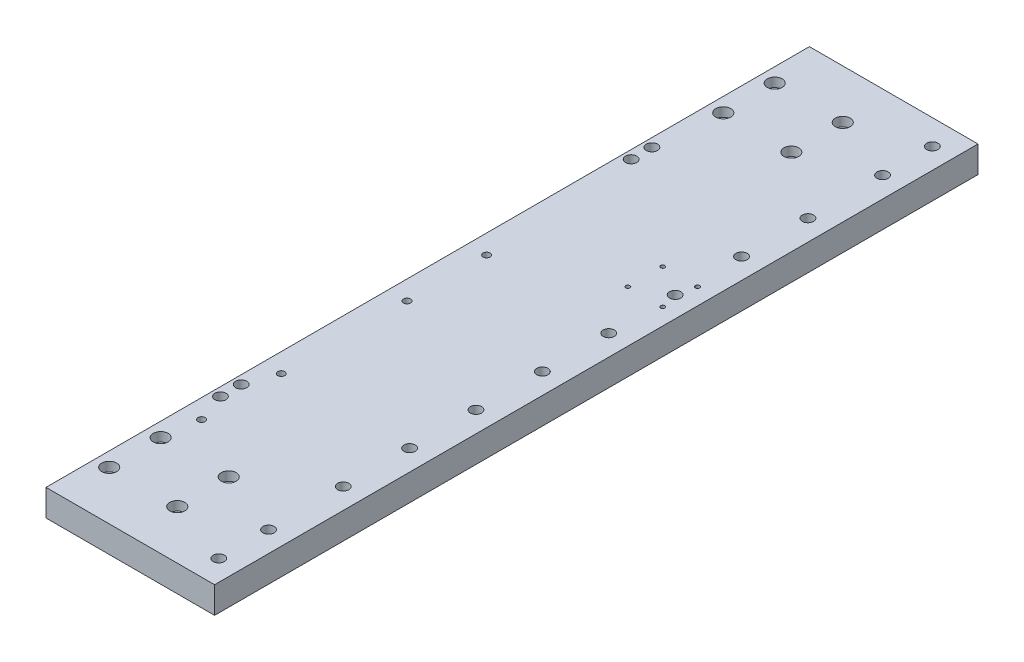
SolidWorks part; units mm, degrees
material "Low Carbon Steel"
ref_plane "Front Plane" through (0, 0, 0) normal (0, 0, 1) x (1, 0, 0)
ref_plane "Top Plane" through (0, 0, 0) normal (0, 1, 0) x (1, 0, 0)
ref_plane "Right Plane" through (0, 0, 0) normal (1, 0, 0) x (0, 0, -1)
sketch "Sketch1" plane through (0, 0, 0) normal (0, 1, 0) x (1, 0, 0)
  line L0 (0, 0) -> (0, 920)
  line L1 (0, 920) -> (203.2, 920)
  line L2 (203.2, 920) -> (203.2, 0)
  line L5 (203.2, 0) -> (0, 0)
  dimension "D1" = 920
  dimension "D2" = 203.2
extrude "Boss-Extrude1" add sketch "Sketch1" along normal blind 50.8
sketch "Sketch2" plane through (0, 0, -920) normal (0, 0, -1) x (-1, 0, 0)
  line L1 (-203.2, 5) -> (0, 5)
  line L2 (-203.2, 5) -> (-203.2, 0)
  line L3 (-203.2, 0) -> (0, 0)
  line L4 (0, 5) -> (0, 0)
  line L5 (0, 50.8) -> (0, 0) construction
  dimension "D1" = 5
extrude "Cut-Extrude1" cut sketch "Sketch2" against normal through all
sketch "Sketch6" plane through (0, 0, -920) normal (0, 0, -1) x (-1, 0, 0)
  line L1 (-203.2, 37) -> (52.8, 37)
  line L2 (-203.2, 37) -> (-203.2, 50.8)
  line L3 (-203.2, 50.8) -> (52.8, 50.8)
  line L4 (52.8, 37) -> (52.8, 50.8)
  line L5 (0, 5) -> (-203.2, 5) construction
  dimension "D1" = 256
  dimension "D2" = 32
extrude "Cut-Extrude3" cut sketch "Sketch6" against normal through all
hole_wizard "M12 Clearance Hole1" positions "Sketch8" profile "Sketch7" hole size "M12" standard "Peddi DIN" end condition through all
sketch "Sketch8" plane through (7.928, 37, -192.8709) normal (0, -1, 0) x (-1, 0, 0)
  line L0 (-170.272, 727.1291) -> (-170.272, -192.8709) construction
  line L6 (-195.272, 727.1291) -> (7.928, 727.1291) construction
  line L7 (-195.272, -192.8709) -> (-195.272, 727.1291) construction
  line L9 (-195.272, -192.8709) -> (7.928, -192.8709) construction
  point P10 (-170.272, 697.1291)
  point P12 (-170.272, 637.1291)
  point P14 (-170.272, 547.1291)
  point P16 (-170.272, 467.1291)
  point P18 (-170.272, 307.1291)
  point P29 (-170.272, 147.1291)
  point P32 (-170.272, 67.1291)
  point P41 (-170.272, -102.8709)
  point P42 (-170.272, 387.1291)
  point P44 (-170.272, 227.1291)
  point P46 (-170.272, -12.8709)
  point P49 (-170.272, -162.8709)
  dimension "D1" = 30
  dimension "D2" = 25
  dimension "D3" = 60
  dimension "D4" = 90
  dimension "D5" = 80
  dimension "D6" = 80
  dimension "D7" = 80
  dimension "D8" = 80
  dimension "D9" = 80
  dimension "D10" = 80
  dimension "D11" = 80
  dimension "D12" = 90
  dimension "D13" = 60
sketch "Sketch7" plane through (178.2, 37, -30) normal (1, 0, 0) x (0, 0, 1)
  line L0 (0, 0) -> (0, 32)
  line L1 (0, 32) -> (6.75, 32)
  line L2 (6.75, 32) -> (6.75, 0)
  line L5 (6.75, 0) -> (0, 0)
  line L11 (0, -6.35) -> (0, 107.95) construction
  dimension "Thru Hole Dia." = 13.5
  dimension "Thru Hole Depth" = 32
hole_wizard "CBORE for M10 Hex Socket Head Cap Screw1" positions "Sketch10" profile "Sketch9" counterbore size "M10" standard "Peddi DIN" end condition through all
sketch "Sketch10" plane through (-145.4119, 37, -401.6366) normal (0, 1, 0) x (1, 0, 0)
  line L1 (162.6119, -280.6366) -> (244.6119, -280.6366) construction
  line L2 (162.6119, -280.6366) -> (162.6119, -342.6366) construction
  line L3 (162.6119, -342.6366) -> (244.6119, -342.6366) construction
  line L4 (244.6119, -280.6366) -> (244.6119, -342.6366) construction
  line L6 (162.6119, 459.3634) -> (244.6119, 459.3634) construction
  line L7 (162.6119, 459.3634) -> (162.6119, 397.3634) construction
  line L8 (162.6119, 397.3634) -> (244.6119, 397.3634) construction
  line L9 (244.6119, 459.3634) -> (244.6119, 397.3634) construction
  line L10 (203.6119, -342.6366) -> (203.6119, -42.6186) construction
  line L13 (603.6119, 342.6735) -> (603.6119, 12.6437) construction
  line L17 (244.6119, 397.3634) -> (244.6119, -280.6366) construction
  line L20 (244.6119, 58.3634) -> (145.4119, 58.3634) construction
  line L22 (145.4119, -401.6366) -> (145.4119, 518.3634) construction
  circle A0 centre (323.6119, 98.3634) radius 6.75 construction
  point P1 (162.6119, -280.6366)
  point P2 (244.6119, -342.6366)
  point P39 (162.6119, -342.6366)
  point P40 (244.6119, -280.6366)
  point P41 (162.6119, 459.3634)
  point P42 (244.6119, 397.3634)
  point P101 (162.6119, 397.3634)
  point P102 (244.6119, 459.3634)
  dimension "D1" = 280
  dimension "D2" = 400
  dimension "D3" = 82
  dimension "D4" = 62
  dimension "D6" = 740
sketch "Sketch9" plane through (17.2, 37, -121) normal (1, 0, 0) x (0, 0, 1)
  line L0 (0, 0) -> (0, 32)
  line L1 (0, 32) -> (5.5, 32)
  line L3 (5.5, 32) -> (5.5, 11)
  line L4 (5.5, 11) -> (9, 11)
  line L5 (9, 11) -> (9, 0)
  line L7 (9, 0) -> (0, 0)
  line L11 (0, -6.35) -> (0, 107.95) construction
  dimension "Thru Hole Dia." = 11
  dimension "Thru Hole Depth" = 32
  dimension "C'Bore Dia." = 18
  dimension "C'Bore Depth" = 11
hole_wizard "M6 Tapped Hole1" positions "Sketch12" profile "Sketch11" tap size "M6" standard "Peddi DIN"
sketch "Sketch12" plane through (0, 5, 0) normal (0, 1, 0) x (1, 0, 0)
  line L0 (10.2, 200) -> (10.2, 225) construction
  line L1 (10.2, 225) -> (10.2, 695) construction
  line L2 (10.2, 695) -> (10.2, 720) construction
  line L6 (203.2, 460) -> (10.2, 460) construction
  line L7 (203.2, 0) -> (203.2, 920) construction
  circle A0 centre (178.2, 500) radius 6.75 construction
  point P0 (10.2, 720)
  point P2 (10.2, 695)
  point P4 (10.2, 200)
  point P6 (10.2, 225)
  dimension "D3" = 168
  dimension "D1" = 25
  dimension "D2" = 470
cosmetic thread "Hole Thread1" parameters "D1"=12, "D2"=6
cosmetic thread "Hole Thread2" parameters "D1"=12, "D2"=6
cosmetic thread "Hole Thread13" parameters "D1"=12, "D2"=6
cosmetic thread "Hole Thread14" parameters "D1"=12, "D2"=6
sketch "Sketch11" plane through (10.2, 5, -720) normal (1, 0, 0) x (0, 0, -1)
  line L0 (0, 0) -> (0, 29.4922)
  line L1 (0, 29.4922) -> (2.5, 27.99)
  line L2 (2.5, 27.99) -> (2.5, 0)
  line L5 (2.5, 0) -> (0, 0)
  line L10 (0, 29.4922) -> (-2.5, 27.99) construction
  line L11 (0, -6.35) -> (0, 107.95) construction
  dimension "Tap Drill Dia." = 5
  dimension "Tap Drill Depth" = 27.99
  dimension "Drill Angle" = 118
hole_wizard "M6 Tapped Hole2" positions "Sketch14" profile "Sketch13" tap size "M6" standard "Peddi DIN"
sketch "Sketch14" plane through (0, 37, 0) normal (0, 1, 0) x (1, 0, 0)
  line L0 (141.2, 602) -> (183.2, 602) construction
  line L1 (183.2, 602) -> (183.2, 560) construction
  line L2 (203.2, 920) -> (0, 920) construction
  circle A0 centre (178.2, 660) radius 6.75 construction
  point P0 (141.2, 560)
  point P2 (183.2, 602)
  point P4 (141.2, 602)
  point P21 (183.2, 560)
  dimension "D3" = 5
  dimension "D4" = 318
  dimension "D1" = 42
  dimension "D2" = 42
sketch "Sketch13" plane through (141.2, 37, -560) normal (1, 0, 0) x (0, 0, 1)
  line L0 (0, 0) -> (0, 29.4922)
  line L1 (0, 29.4922) -> (2.5, 27.99)
  line L2 (2.5, 27.99) -> (2.5, 0)
  line L5 (2.5, 0) -> (0, 0)
  line L10 (0, 29.4922) -> (-2.5, 27.99) construction
  line L11 (0, -6.35) -> (0, 107.95) construction
  dimension "Tap Drill Dia." = 5
  dimension "Tap Drill Depth" = 27.99
  dimension "Drill Angle" = 118
cosmetic thread "Hole Thread5" parameters "D1"=15.01, "D2"=6
cosmetic thread "Hole Thread6" parameters "D1"=15.01, "D2"=6
cosmetic thread "Hole Thread7" parameters "D1"=15.01, "D2"=6
cosmetic thread "Hole Thread8" parameters "D1"=15.01, "D2"=6
hole_wizard "Ø13.5 (13.5) Diameter Hole1" positions "Sketch16" profile "Sketch15" hole size "Ø13.5" standard "Peddi DIN"
sketch "Sketch16" plane through (0, 37, 0) normal (0, 1, 0) x (1, 0, 0)
  point P0 (10.2, 720)
  point P3 (10.2, 695)
  point P6 (10.2, 225)
  point P9 (10.2, 200)
sketch "Sketch15" plane through (10.2, 37, -720) normal (1, 0, 0) x (0, 0, 1)
  line L0 (0, 0) -> (0, 24.0558)
  line L1 (0, 24.0558) -> (6.75, 20)
  line L2 (6.75, 20) -> (6.75, 0)
  line L5 (6.75, 0) -> (0, 0)
  line L10 (0, 24.0558) -> (-6.75, 20) construction
  line L11 (0, -6.35) -> (0, 107.95) construction
  dimension "Hole Dia." = 13.5
  dimension "Hole Depth" = 20
  dimension "Drill Angle" = 118
hole_wizard "M10 Tapped Hole1" positions "Sketch18" profile "Sketch17" tap size "M10" standard "Peddi DIN"
sketch "Sketch18" plane through (0, 37, 0) normal (0, 1, 0) x (1, 0, 0)
  line L0 (203.2, 460) -> (0, 460) construction
  line L1 (203.2, 0) -> (203.2, 920) construction
  line L2 (0, 0) -> (0, 920) construction
  line L4 (10.2, 225) -> (10.2, 200) construction
  line L6 (10.2, 212.5) -> (23, 212.5) construction
  line L8 (23, 260.5) -> (23, 164.5) construction
  circle A0 centre (178.2, 30) radius 6.75 construction
  point P0 (23, 164.5)
  point P5 (23, 260.5)
  point P12 (23, 508)
  point P14 (23, 412)
  dimension "D1" = 96
  dimension "D2" = 155.2
  dimension "D4" = 96
  dimension "D5" = 48
sketch "Sketch17" plane through (23, 37, -164.5) normal (1, 0, 0) x (0, 0, 1)
  line L0 (0, 0) -> (0, 40.5537)
  line L1 (0, 40.5537) -> (4.25, 38)
  line L2 (4.25, 38) -> (4.25, 0)
  line L5 (4.25, 0) -> (0, 0)
  line L10 (0, 40.5537) -> (-4.25, 38) construction
  line L11 (0, -6.35) -> (0, 107.95) construction
  dimension "Tap Drill Dia." = 8.5
  dimension "Tap Drill Depth" = 38
  dimension "Drill Angle" = 118
cosmetic thread "Hole Thread15" parameters "D1"=24.99, "D2"=10
cosmetic thread "Hole Thread16" parameters "D1"=24.99, "D2"=10
cosmetic thread "Hole Thread17" parameters "D1"=24.99, "D2"=10
cosmetic thread "Hole Thread18" parameters "D1"=24.99, "D2"=10
other "Freeze***"
equation "\"D4@Sketch18\"=\"D1@Sketch18\""
equation "\"D5@Sketch18\"=\"D1@Sketch18\"/2"
